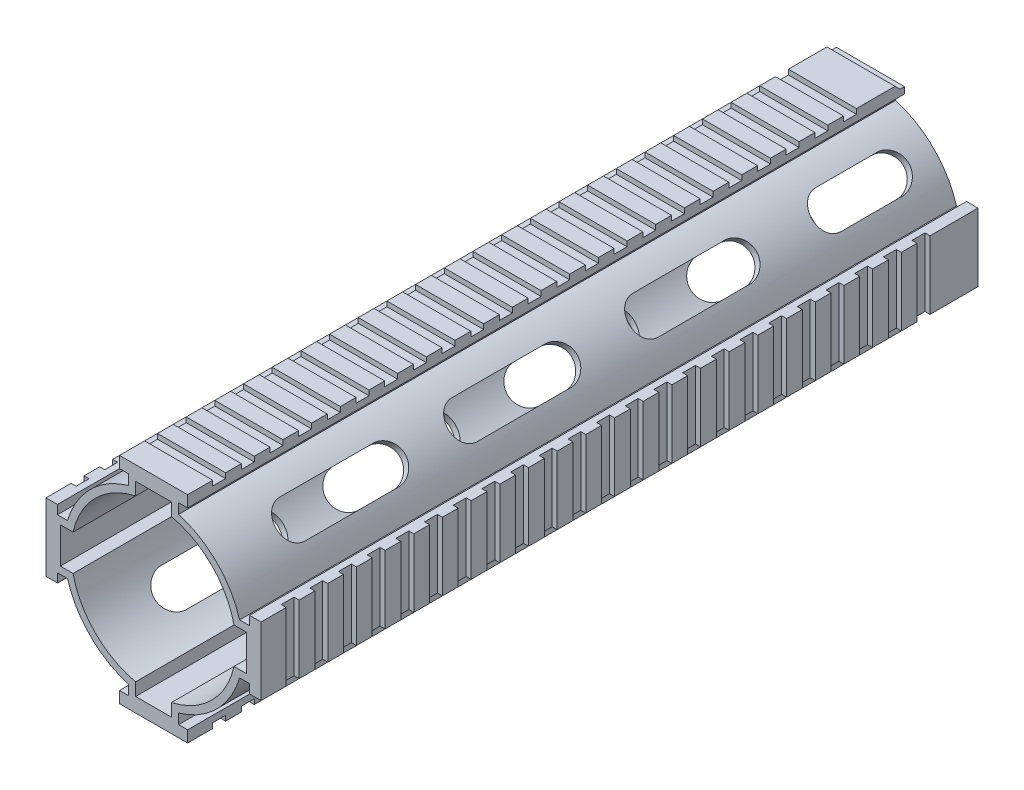
SolidWorks part; units mm, degrees
ref_plane "前视基准面" through (0, 0, 0) normal (0, 0, 1) x (1, 0, 0)
ref_plane "上视基准面" through (0, 0, 0) normal (0, 1, 0) x (1, 0, 0)
ref_plane "右视基准面" through (0, 0, 0) normal (1, 0, 0) x (0, 0, -1)
other "Configuration Table"
sketch "草图1" plane through (0, 0, 0) normal (0, 0, 1) x (1, 0, 0)
  line L0 (0, 26) -> (0, -26) construction
  line L2 (-5, -22.4499) -> (-5, -26)
  line L3 (-5, -26) -> (5, -26)
  line L4 (5, -22.4499) -> (5, -26)
  line L5 (-22.4499, -5) -> (-26, -5)
  line L6 (-26, 5) -> (-26, -5)
  line L7 (-22.4499, 5) -> (-26, 5)
  line L8 (-5, 22.4499) -> (-5, 26)
  line L9 (5, 26) -> (-5, 26)
  line L10 (5, 22.4499) -> (5, 26)
  line L11 (22.4499, 5) -> (26, 5)
  line L12 (26, -5) -> (26, 5)
  line L13 (22.4499, -5) -> (26, -5)
  arc A0 (5, -22.4499) -> (22.4499, -5) centre (0, 0) ccw
  arc A1 (22.4499, 5) -> (5, 22.4499) centre (0, 0) ccw
  arc A2 (-5, 22.4499) -> (-22.4499, 5) centre (0, 0) ccw
  arc A3 (-22.4499, -5) -> (-5, -22.4499) centre (0, 0) ccw
  point P10 (0, 0)
  dimension "D1" = 46
  dimension "D3" = 10
  dimension "D4" = 52
  dimension "D2" = 4
sketch "草图2" plane through (0, 0, 0) normal (0, 0, 1) x (1, 0, 0)
  line L0 (0, 26) -> (0, -26) construction
  line L2 (-7, -24) -> (-7, -26.8)
  line L4 (7, -24) -> (7, -26.8)
  line L5 (0, 25) -> (0, -30) construction
  line L6 (7, -26.8) -> (9.5, -26.8)
  line L7 (-9.5, -26.8) -> (-7, -26.8)
  line L8 (-9.5, -26.8) -> (-9.5, -30)
  line L9 (-9.5, -30) -> (9.5, -30)
  line L10 (9.5, -26.8) -> (9.5, -30)
  line L11 (-24, 7) -> (-26.8, 7)
  line L12 (-26.8, 9.5) -> (-26.8, 7)
  line L13 (-26.8, 9.5) -> (-30, 9.5)
  line L14 (-30, 9.5) -> (-30, -9.5)
  line L15 (-26.8, -9.5) -> (-30, -9.5)
  line L16 (-26.8, -7) -> (-26.8, -9.5)
  line L17 (-24, -7) -> (-26.8, -7)
  line L18 (7, 24) -> (7, 26.8)
  line L19 (9.5, 26.8) -> (7, 26.8)
  line L20 (9.5, 26.8) -> (9.5, 30)
  line L21 (9.5, 30) -> (-9.5, 30)
  line L22 (-9.5, 26.8) -> (-9.5, 30)
  line L23 (-7, 26.8) -> (-9.5, 26.8)
  line L24 (-7, 24) -> (-7, 26.8)
  line L25 (24, -7) -> (26.8, -7)
  line L26 (26.8, -9.5) -> (26.8, -7)
  line L27 (26.8, -9.5) -> (30, -9.5)
  line L28 (30, -9.5) -> (30, 9.5)
  line L29 (26.8, 9.5) -> (30, 9.5)
  line L30 (26.8, 7) -> (26.8, 9.5)
  line L31 (24, 7) -> (26.8, 7)
  line L32 (-22.4499, 5) -> (-26, 5) construction
  line L33 (-26, 5) -> (-26, -5) construction
  line L34 (-22.4499, -5) -> (-26, -5) construction
  line L35 (-5, -22.4499) -> (-5, -26) construction
  line L36 (-5, -26) -> (5, -26) construction
  line L37 (5, -22.4499) -> (5, -26) construction
  line L38 (22.4499, -5) -> (26, -5) construction
  line L39 (26, -5) -> (26, 5) construction
  line L40 (22.4499, 5) -> (26, 5) construction
  line L41 (5, 22.4499) -> (5, 26) construction
  line L42 (5, 26) -> (-5, 26) construction
  line L43 (-5, 22.4499) -> (-5, 26) construction
  line L44 (-22.4499, 5) -> (-26, 5)
  line L45 (-26, 5) -> (-26, -5)
  line L46 (-22.4499, -5) -> (-26, -5)
  line L47 (-5, -22.4499) -> (-5, -26)
  line L48 (-5, -26) -> (5, -26)
  line L49 (5, -22.4499) -> (5, -26)
  line L50 (22.4499, -5) -> (26, -5)
  line L51 (26, -5) -> (26, 5)
  line L52 (22.4499, 5) -> (26, 5)
  line L53 (5, 22.4499) -> (5, 26)
  line L54 (5, 26) -> (-5, 26)
  line L55 (-5, 22.4499) -> (-5, 26)
  arc A0 (7, -24) -> (24, -7) centre (0, 0) ccw
  arc A1 (-24, -7) -> (-7, -24) centre (0, 0) ccw
  arc A2 (-7, 24) -> (-24, 7) centre (0, 0) ccw
  arc A3 (24, 7) -> (7, 24) centre (0, 0) ccw
  arc A4 (-5, 22.4499) -> (-22.4499, 5) centre (0, 0) ccw construction
  arc A5 (-22.4499, -5) -> (-5, -22.4499) centre (0, 0) ccw construction
  arc A6 (5, -22.4499) -> (22.4499, -5) centre (0, 0) ccw construction
  arc A7 (22.4499, 5) -> (5, 22.4499) centre (0, 0) ccw construction
  arc A8 (-5, 22.4499) -> (-22.4499, 5) centre (0, 0) ccw
  arc A9 (-22.4499, -5) -> (-5, -22.4499) centre (0, 0) ccw
  arc A10 (5, -22.4499) -> (22.4499, -5) centre (0, 0) ccw
  arc A11 (22.4499, 5) -> (5, 22.4499) centre (0, 0) ccw
  dimension "D1" = 50
  dimension "D3" = 14
  dimension "D4" = 19
  dimension "D5" = 60
  dimension "D6" = 2.8
  dimension "D2" = 4
extrude "凸台-拉伸1" add sketch "草图2" against normal blind 200
ref_plane "基准面1" through (-13.725, 13.725, 0) normal (0.7071, -0.7071, 0) x (-0.7071, -0.7071, 0)
sketch "草图3" plane through (-13.725, 13.725, 0) normal (0.7071, -0.7071, 0) x (-0.7071, -0.7071, 0)
  line L0 (0, 200) -> (0, 0) construction
  line L1 (12.0208, 200) -> (-12.0208, 200) construction
  line L2 (0, 21.5) -> (0, 47.5) construction
  line L3 (-5, 21.5) -> (-5, 47.5)
  line L4 (5, 21.5) -> (5, 47.5)
  line L5 (0, 69.5) -> (0, 95.5) construction
  line L6 (-5, 69.5) -> (-5, 95.5)
  line L7 (5, 69.5) -> (5, 95.5)
  line L8 (0, 120) -> (0, 145.5) construction
  line L9 (-5, 120) -> (-5, 145.5)
  line L10 (5, 120) -> (5, 145.5)
  line L11 (0, 171) -> (0, 188) construction
  line L12 (-5, 171) -> (-5, 188)
  line L13 (5, 171) -> (5, 188)
  arc A0 (-5, 21.5) -> (5, 21.5) centre (0, 21.5) ccw
  arc A1 (5, 47.5) -> (-5, 47.5) centre (0, 47.5) ccw
  arc A2 (-5, 69.5) -> (5, 69.5) centre (0, 69.5) ccw
  arc A3 (5, 95.5) -> (-5, 95.5) centre (0, 95.5) ccw
  arc A4 (-5, 120) -> (5, 120) centre (0, 120) ccw
  arc A5 (5, 145.5) -> (-5, 145.5) centre (0, 145.5) ccw
  arc A6 (-5, 171) -> (5, 171) centre (0, 171) ccw
  arc A7 (5, 188) -> (-5, 188) centre (0, 188) ccw
  point P7 (0, 34.5)
  point P12 (0, 82.5)
  point P19 (0, 132.75)
  point P26 (0, 179.5)
  dimension "D9" = 5
  dimension "D1" = 26
  dimension "D2" = 21.5
  dimension "D3" = 22
  dimension "D4" = 26
  dimension "D5" = 24.5
  dimension "D6" = 25.5
  dimension "D7" = 12
  dimension "D8" = 17
extrude "切除-拉伸1" cut sketch "草图3" against normal through all
sketch "草图4" plane through (0, 0, 0) normal (1, 0, 0) x (0, 0, -1)
  line L0 (200, 30) -> (0, 30) construction
  line L1 (7, 30) -> (10.6, 30)
  line L2 (7, 30) -> (7, 28.6)
  line L3 (7, 28.6) -> (10.6, 28.6)
  line L4 (10.6, 30) -> (10.6, 28.6)
  line L5 (0, 30) -> (0, 26.8) construction
  line L10 (15, 30) -> (15, 28.6)
  line L11 (15, 30) -> (18.6, 30)
  line L12 (18.6, 30) -> (18.6, 28.6)
  line L13 (15, 28.6) -> (18.6, 28.6)
  line L14 (23, 30) -> (23, 28.6)
  line L15 (23, 30) -> (26.6, 30)
  line L16 (26.6, 30) -> (26.6, 28.6)
  line L17 (23, 28.6) -> (26.6, 28.6)
  line L18 (31, 30) -> (31, 28.6)
  line L19 (31, 30) -> (34.6, 30)
  line L20 (34.6, 30) -> (34.6, 28.6)
  line L21 (31, 28.6) -> (34.6, 28.6)
  line L22 (39, 30) -> (39, 28.6)
  line L23 (39, 30) -> (42.6, 30)
  line L24 (42.6, 30) -> (42.6, 28.6)
  line L25 (39, 28.6) -> (42.6, 28.6)
  line L26 (47, 30) -> (47, 28.6)
  line L27 (47, 30) -> (50.6, 30)
  line L28 (50.6, 30) -> (50.6, 28.6)
  line L29 (47, 28.6) -> (50.6, 28.6)
  line L30 (55, 30) -> (55, 28.6)
  line L31 (55, 30) -> (58.6, 30)
  line L32 (58.6, 30) -> (58.6, 28.6)
  line L33 (55, 28.6) -> (58.6, 28.6)
  line L34 (63, 30) -> (63, 28.6)
  line L35 (63, 30) -> (66.6, 30)
  line L36 (66.6, 30) -> (66.6, 28.6)
  line L37 (63, 28.6) -> (66.6, 28.6)
  line L38 (71, 30) -> (71, 28.6)
  line L39 (71, 30) -> (74.6, 30)
  line L40 (74.6, 30) -> (74.6, 28.6)
  line L41 (71, 28.6) -> (74.6, 28.6)
  line L42 (79, 30) -> (79, 28.6)
  line L43 (79, 30) -> (82.6, 30)
  line L44 (82.6, 30) -> (82.6, 28.6)
  line L45 (79, 28.6) -> (82.6, 28.6)
  line L46 (87, 30) -> (87, 28.6)
  line L47 (87, 30) -> (90.6, 30)
  line L48 (90.6, 30) -> (90.6, 28.6)
  line L49 (87, 28.6) -> (90.6, 28.6)
  line L50 (95, 30) -> (95, 28.6)
  line L51 (95, 30) -> (98.6, 30)
  line L52 (98.6, 30) -> (98.6, 28.6)
  line L53 (95, 28.6) -> (98.6, 28.6)
  line L54 (103, 30) -> (103, 28.6)
  line L55 (103, 30) -> (106.6, 30)
  line L56 (106.6, 30) -> (106.6, 28.6)
  line L57 (103, 28.6) -> (106.6, 28.6)
  line L58 (111, 30) -> (111, 28.6)
  line L59 (111, 30) -> (114.6, 30)
  line L60 (114.6, 30) -> (114.6, 28.6)
  line L61 (111, 28.6) -> (114.6, 28.6)
  line L62 (119, 30) -> (119, 28.6)
  line L63 (119, 30) -> (122.6, 30)
  line L64 (122.6, 30) -> (122.6, 28.6)
  line L65 (119, 28.6) -> (122.6, 28.6)
  line L66 (127, 30) -> (127, 28.6)
  line L67 (127, 30) -> (130.6, 30)
  line L68 (130.6, 30) -> (130.6, 28.6)
  line L69 (127, 28.6) -> (130.6, 28.6)
  line L70 (135, 30) -> (135, 28.6)
  line L71 (135, 30) -> (138.6, 30)
  line L72 (138.6, 30) -> (138.6, 28.6)
  line L73 (135, 28.6) -> (138.6, 28.6)
  line L74 (143, 30) -> (143, 28.6)
  line L75 (143, 30) -> (146.6, 30)
  line L76 (146.6, 30) -> (146.6, 28.6)
  line L77 (143, 28.6) -> (146.6, 28.6)
  line L78 (151, 30) -> (151, 28.6)
  line L79 (151, 30) -> (154.6, 30)
  line L80 (154.6, 30) -> (154.6, 28.6)
  line L81 (151, 28.6) -> (154.6, 28.6)
  line L82 (159, 30) -> (159, 28.6)
  line L83 (159, 30) -> (162.6, 30)
  line L84 (162.6, 30) -> (162.6, 28.6)
  line L85 (159, 28.6) -> (162.6, 28.6)
  line L86 (167, 30) -> (167, 28.6)
  line L87 (167, 30) -> (170.6, 30)
  line L88 (170.6, 30) -> (170.6, 28.6)
  line L89 (167, 28.6) -> (170.6, 28.6)
  line L90 (175, 30) -> (175, 28.6)
  line L91 (175, 30) -> (178.6, 30)
  line L92 (178.6, 30) -> (178.6, 28.6)
  line L93 (175, 28.6) -> (178.6, 28.6)
  line L94 (183, 30) -> (183, 28.6)
  line L95 (183, 30) -> (186.6, 30)
  line L96 (186.6, 30) -> (186.6, 28.6)
  line L97 (183, 28.6) -> (186.6, 28.6)
  line L102 (191, 30) -> (191, 28.6) [skipped]
  line L103 (194.6, 30) -> (194.6, 28.6) [skipped]
  line L104 (191, 28.6) -> (194.6, 28.6) [skipped]
  line L105 (191, 30) -> (194.6, 30) [skipped]
  point P7 (0, 0)
  dimension "D1" = 1.4
  dimension "D2" = 7
  dimension "D3" = 3.6
  dimension "D5" = 8
  dimension "D4" = 24
extrude "切除-拉伸2" cut sketch "草图4" against normal through all both and the other way through all
sketch "草图5" plane through (0, 0, 0) normal (1, 0, 0) x (0, 0, -1)
  line L0 (200, 28.6) -> (198.75, 28.6)
  line L1 (200, 30) -> (200, 26.8) construction
  line L2 (198.75, 28.6) -> (197.35, 30)
  line L3 (186.6, 28.6) -> (183, 28.6) construction
  line L4 (200, 30) -> (186.6, 30) construction
  line L5 (200, 28.6) -> (200, 30)
  line L6 (200, 30) -> (197.35, 30)
  dimension "D1" = 135
  dimension "D2" = 1.25
extrude "切除-拉伸3" cut sketch "草图5" against normal through all both and the other way through all
pattern_circular "阵列(圆周)1" count 4 over 360 about axis through (0, 0, 0) along (0, 0, 1) of "切除-拉伸1", "切除-拉伸2"
